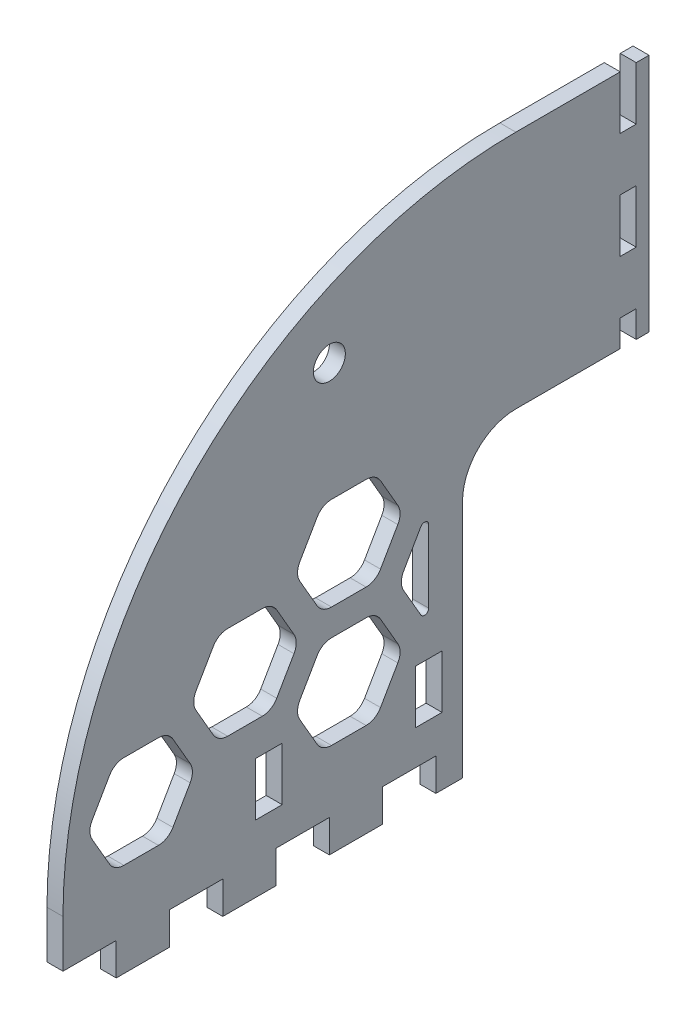
SolidWorks part; units mm, degrees
material "Pine"
ref_plane "Front Plane" through (0, 0, 0) normal (0, 0, 1) x (1, 0, 0)
ref_plane "Top Plane" through (0, 0, 0) normal (0, 1, 0) x (1, 0, 0)
ref_plane "Right Plane" through (0, 0, 0) normal (1, 0, 0) x (0, 0, -1)
sketch "Sketch1" plane through (0, 0, 0) normal (1, 0, 0) x (0, 0, -1)
  line L1 (0, 0) -> (110, 0)
  line L2 (0, 0) -> (0, 15)
  line L3 (85, 100) -> (110, 100)
  line L4 (110, 0) -> (110, 100)
  arc A0 (0, 15) -> (85, 100) centre (85, 15) cw
  circle A1 centre (50, 80) radius 3
  point P7 (0, 100)
  dimension "D3" = 85
  dimension "D4" = 80
  dimension "D6" = 6
  dimension "D1" = 100
  dimension "D2" = 110
  dimension "D5" = 50
extrude "Boss-Extrude1" add sketch "Sketch1" along normal blind 3
sketch "Sketch2" plane through (3, 0, 0) normal (1, 0, 0) x (0, 0, -1)
  line L1 (110, 0) -> (75, 0)
  line L2 (110, 0) -> (110, 55)
  line L3 (110, 55) -> (85, 55)
  line L4 (75, 0) -> (75, 45)
  arc A0 (85, 55) -> (75, 45) centre (85, 45) ccw
  point P7 (75, 55)
  dimension "D3" = 10
  dimension "D1" = 55
  dimension "D2" = 35
extrude "Cut-Extrude1" cut sketch "Sketch2" against normal through all both and the other way through all
sketch "Sketch4" plane through (3, 0, 0) normal (1, 0, 0) x (0, 0, -1)
  line L0 (20, 0) -> (30, 0)
  line L1 (0, 0) -> (10, 0)
  line L2 (0, 0) -> (0, 6.1)
  line L3 (0, 6.1) -> (10, 6.1)
  line L4 (10, 0) -> (10, 6.1)
  line L5 (20, 0) -> (20, 6.1)
  line L6 (20, 6.1) -> (30, 6.1)
  line L7 (30, 0) -> (30, 6.1)
  line L8 (40, 0) -> (50, 0)
  line L9 (40, 0) -> (40, 6.1)
  line L10 (40, 6.1) -> (50, 6.1)
  line L11 (50, 0) -> (50, 6.1)
  line L12 (60, 0) -> (70, 0)
  line L13 (60, 0) -> (60, 6.1)
  line L14 (60, 6.1) -> (70, 6.1)
  line L15 (70, 0) -> (70, 6.1)
  line L16 (0, 0) -> (20, 0) construction
  dimension "D1" = 6.1
  dimension "D2" = 10
  dimension "D4" = 20
  dimension "D3" = 4
extrude "Cut-Extrude2" cut sketch "Sketch4" against normal through all both and the other way through all
sketch "Sketch5" plane through (0, 0, 0) normal (-1, 0, 0) x (0, 0, 1)
  line L1 (-71.15, 22.6) -> (-66.15, 22.6)
  line L2 (-71.15, 22.6) -> (-71.15, 12.6)
  line L3 (-71.15, 12.6) -> (-66.15, 12.6)
  line L4 (-66.15, 22.6) -> (-66.15, 12.6)
  line L5 (-66.15, 12.6) -> (-71.15, 12.6) construction
  line L7 (-41.15, 22.6) -> (-36.15, 22.6)
  line L8 (-41.15, 22.6) -> (-41.15, 12.6)
  line L9 (-41.15, 12.6) -> (-36.15, 12.6)
  line L10 (-36.15, 22.6) -> (-36.15, 12.6)
extrude "Cut-Extrude3" cut sketch "Sketch5" against normal through all both and the other way through all
sketch "Sketch6" plane through (3, 0, 0) normal (1, 0, 0) x (0, 0, -1)
  line L0 (110, 100) -> (85, 100) construction
  line L1 (104.6, 90) -> (107.6, 90)
  line L2 (104.6, 90) -> (104.6, 100)
  line L3 (104.6, 100) -> (107.6, 100)
  line L4 (107.6, 90) -> (107.6, 100)
  line L5 (107.6, 90) -> (107.6, 100) construction
  line L7 (104.6, 80) -> (107.6, 80)
  line L8 (104.6, 80) -> (104.6, 70)
  line L9 (104.6, 70) -> (107.6, 70)
  line L10 (107.6, 80) -> (107.6, 70)
  line L11 (104.6, 60) -> (107.6, 60)
  line L12 (104.6, 60) -> (104.6, 45)
  line L13 (104.6, 45) -> (107.6, 45)
  line L14 (107.6, 60) -> (107.6, 45)
extrude "Cut-Extrude4" cut sketch "Sketch6" against normal through all
sketch "Sketch7" plane through (3, 0, 0) normal (1, 0, 0) x (0, 0, -1)
  line L1 (62.8515, 50.4125) -> (59.6039, 56.0375)
  line L2 (56.8976, 57.6) -> (50.4024, 57.6)
  line L3 (47.6961, 56.0375) -> (44.4485, 50.4125)
  line L4 (44.4485, 47.2875) -> (47.6961, 41.6625)
  line L5 (50.4024, 40.1) -> (56.8976, 40.1)
  line L6 (59.6039, 41.6625) -> (62.8515, 47.2875)
  line L8 (67.1816, 44.7875) -> (63.9341, 39.1625)
  line L9 (63.9341, 36.0375) -> (67.1816, 30.4125)
  line L12 (68.6395, 44.3969) -> (68.6395, 30.8031)
  line L13 (62.8515, 27.9125) -> (59.6039, 33.5375)
  line L14 (56.8976, 35.1) -> (50.4024, 35.1)
  line L15 (47.6961, 33.5375) -> (44.4485, 27.9125)
  line L16 (44.4485, 24.7875) -> (47.6961, 19.1625)
  line L17 (50.4024, 17.6) -> (56.8976, 17.6)
  line L18 (59.6039, 19.1625) -> (62.8515, 24.7875)
  line L19 (41.15, 17.6) -> (66.15, 17.6) construction
  line L20 (41.15, 22.6) -> (41.15, 12.6) construction
  line L21 (66.15, 12.6) -> (66.15, 22.6) construction
  line L22 (53.65, 17.6) -> (53.65, 26.35) construction
  line L23 (43.3659, 39.1625) -> (40.1184, 44.7875)
  line L24 (37.412, 46.35) -> (30.9168, 46.35)
  line L25 (28.2105, 44.7875) -> (24.9629, 39.1625)
  line L26 (24.9629, 36.0375) -> (28.2105, 30.4125)
  line L27 (30.9168, 28.85) -> (37.412, 28.85)
  line L28 (40.1184, 30.4125) -> (43.3659, 36.0375)
  line L29 (23.8804, 27.9125) -> (20.6328, 33.5375)
  line L30 (17.9265, 35.1) -> (11.4313, 35.1)
  line L31 (8.7249, 33.5375) -> (5.4773, 27.9125)
  line L32 (5.4773, 24.7875) -> (8.7249, 19.1625)
  line L33 (11.4313, 17.6) -> (17.9265, 17.6)
  line L34 (20.6328, 19.1625) -> (23.8804, 24.7875)
  circle A0 centre (53.65, 48.85) radius 8.75 construction
  arc A1 (56.8976, 40.1) -> (59.6039, 41.6625) centre (56.8976, 43.225) ccw
  arc A2 (47.6961, 41.6625) -> (50.4024, 40.1) centre (50.4024, 43.225) ccw
  arc A3 (44.4485, 50.4125) -> (44.4485, 47.2875) centre (47.1548, 48.85) ccw
  arc A4 (50.4024, 57.6) -> (47.6961, 56.0375) centre (50.4024, 54.475) ccw
  arc A5 (59.6039, 56.0375) -> (56.8976, 57.6) centre (56.8976, 54.475) ccw
  arc A6 (62.8515, 50.4125) -> (62.8515, 47.2875) centre (60.1452, 48.85) cw
  arc A7 (68.6395, 45.1065) -> (68.6395, 30.0935) centre (73.1356, 37.6) ccw construction
  arc A10 (63.9341, 39.1625) -> (63.9341, 36.0375) centre (66.6404, 37.6) ccw
  arc A12 (68.6395, 44.3969) -> (67.1816, 44.7875) centre (67.8582, 44.3969) ccw
  arc A13 (67.1816, 30.4125) -> (68.6395, 30.8031) centre (67.8582, 30.8031) ccw
  arc A14 (56.8976, 17.6) -> (59.6039, 19.1625) centre (56.8976, 20.725) ccw
  arc A15 (47.6961, 19.1625) -> (50.4024, 17.6) centre (50.4024, 20.725) ccw
  arc A16 (44.4485, 27.9125) -> (44.4485, 24.7875) centre (47.1548, 26.35) ccw
  arc A17 (50.4024, 35.1) -> (47.6961, 33.5375) centre (50.4024, 31.975) ccw
  arc A18 (59.6039, 33.5375) -> (56.8976, 35.1) centre (56.8976, 31.975) ccw
  arc A19 (62.8515, 27.9125) -> (62.8515, 24.7875) centre (60.1452, 26.35) cw
  circle A20 centre (53.65, 26.35) radius 8.75 construction
  circle A21 centre (34.1644, 37.6) radius 8.75 construction
  arc A22 (37.412, 28.85) -> (40.1184, 30.4125) centre (37.412, 31.975) ccw
  arc A23 (28.2105, 30.4125) -> (30.9168, 28.85) centre (30.9168, 31.975) ccw
  arc A24 (24.9629, 39.1625) -> (24.9629, 36.0375) centre (27.6692, 37.6) ccw
  arc A25 (30.9168, 46.35) -> (28.2105, 44.7875) centre (30.9168, 43.225) ccw
  arc A26 (40.1184, 44.7875) -> (37.412, 46.35) centre (37.412, 43.225) ccw
  arc A27 (43.3659, 39.1625) -> (43.3659, 36.0375) centre (40.6596, 37.6) cw
  arc A28 (17.9265, 17.6) -> (20.6328, 19.1625) centre (17.9265, 20.725) ccw
  arc A29 (8.7249, 19.1625) -> (11.4313, 17.6) centre (11.4313, 20.725) ccw
  arc A30 (5.4773, 27.9125) -> (5.4773, 24.7875) centre (8.1837, 26.35) ccw
  arc A31 (11.4313, 35.1) -> (8.7249, 33.5375) centre (11.4313, 31.975) ccw
  arc A32 (20.6328, 33.5375) -> (17.9265, 35.1) centre (17.9265, 31.975) ccw
  arc A33 (23.8804, 27.9125) -> (23.8804, 24.7875) centre (21.174, 26.35) cw
  circle A34 centre (14.6789, 26.35) radius 8.75 construction
  dimension "D1" = 17.5
  dimension "D2" = 3.125
  dimension "D3" = 17.5
  dimension "D4" = 0.7812
  dimension "D9" = 17.5
  dimension "D10" = 2
  dimension "D5" = 5
  dimension "D7" = 5
  dimension "D8" = 5
  dimension "D11" = 5
  dimension "D12" = 5
  dimension "D6" = 2
extrude "Cut-Extrude5" cut sketch "Sketch7" against normal through all
